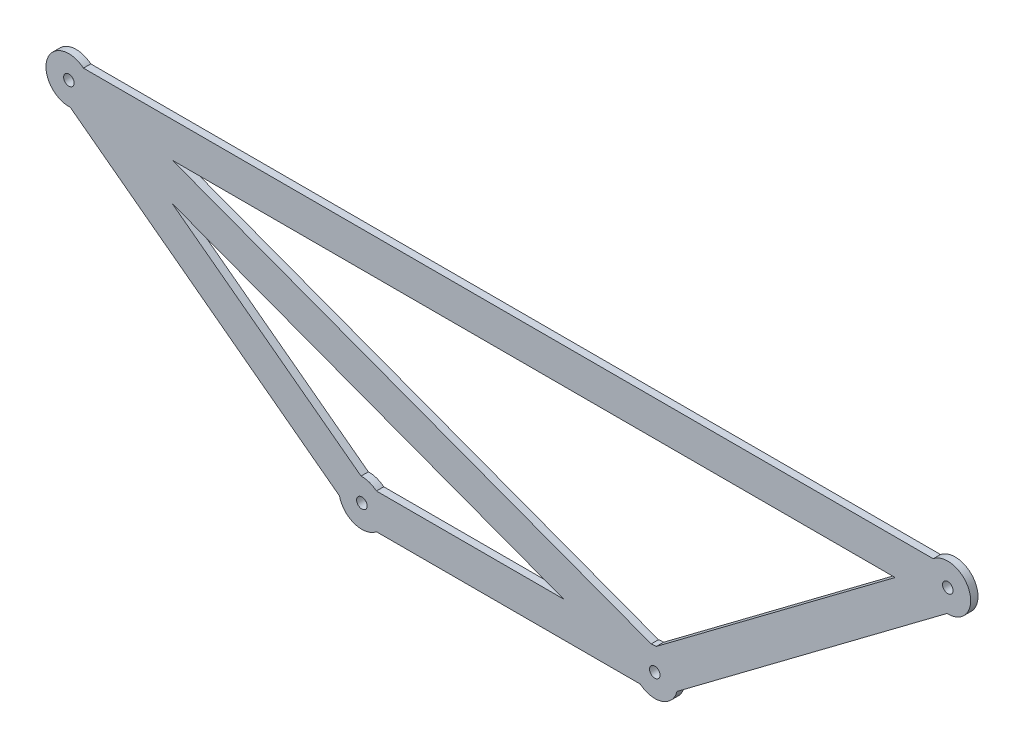
SolidWorks part; units mm, degrees
material "ASTM A36 Steel"
ref_plane "Front Plane" through (0, 0, 0) normal (0, 0, 1) x (1, 0, 0)
ref_plane "Top Plane" through (0, 0, 0) normal (0, 1, 0) x (1, 0, 0)
ref_plane "Right Plane" through (0, 0, 0) normal (1, 0, 0) x (0, 0, -1)
sketch "Sketch2" plane through (0, 0, 0) normal (0, 0, 1) x (1, 0, 0)
  line L0 (0, 0) -> (1200, 0) construction
  line L1 (600, 0) -> (600, -300) construction
  line L2 (400, -300) -> (800, -300) construction
  line L3 (0, 0) -> (400, -300) construction
  line L4 (1200, 0) -> (800, -300) construction
  line L5 (0, 0) -> (800, -300) construction
  line L6 (400, -324.1) -> (800, -324.1)
  line L7 (400, -324.1) -> (400, -275.9)
  line L8 (400, -275.9) -> (800, -275.9)
  line L9 (800, -324.1) -> (800, -275.9)
  line L10 (400, -324.1) -> (800, -275.9) construction
  line L11 (400, -275.9) -> (800, -324.1) construction
  line L12 (0, -24.1) -> (1200, -24.1)
  line L13 (0, -24.1) -> (0, 24.1)
  line L14 (0, 24.1) -> (1200, 24.1)
  line L15 (1200, -24.1) -> (1200, 24.1)
  line L16 (0, -24.1) -> (1200, 24.1) construction
  line L17 (0, 24.1) -> (1200, -24.1) construction
  line L18 (414.6104, -280.5195) -> (14.6104, 19.4805)
  line L19 (414.6104, -280.5195) -> (385.6904, -319.0795)
  line L20 (14.6104, 19.4805) -> (-14.3096, -19.0795)
  line L21 (385.6904, -319.0795) -> (-14.3096, -19.0795)
  line L22 (414.6104, -280.5195) -> (-14.3096, -19.0795) construction
  line L23 (14.6104, 19.4805) -> (385.6904, -319.0795) construction
  line L24 (1185.6877, 19.0831) -> (785.6877, -280.9169)
  line L25 (1185.6877, 19.0831) -> (1214.6077, -19.4769)
  line L26 (785.6877, -280.9169) -> (814.6077, -319.4769)
  line L27 (1214.6077, -19.4769) -> (814.6077, -319.4769)
  line L28 (1185.6877, 19.0831) -> (814.6077, -319.4769) construction
  line L29 (785.6877, -280.9169) -> (1214.6077, -19.4769) construction
  line L30 (792.6095, -319.7081) -> (-7.3905, -19.7081)
  line L31 (792.6095, -319.7081) -> (809.5336, -274.577)
  line L32 (-7.3905, -19.7081) -> (9.5336, 25.423)
  line L33 (809.5336, -274.577) -> (9.5336, 25.423)
  line L34 (792.6095, -319.7081) -> (9.5336, 25.423) construction
  line L35 (-7.3905, -19.7081) -> (809.5336, -274.577) construction
  circle A0 centre (400, -300) radius 31.26
  circle A1 centre (800, -300) radius 31.26
  circle A2 centre (0, 0) radius 31.26
  circle A3 centre (1200, 0) radius 31.26
  point P8 (600, -300)
  point P17 (200.1504, -149.7995)
  point P18 (1000.1477, -150.1969)
  point P23 (401.0716, -147.1425)
  dimension "D10" = 62.52
  dimension "D11" = 62.52
  dimension "D12" = 62.52
  dimension "D13" = 62.52
  dimension "D1" = 1200
  dimension "D2" = 400
  dimension "D3" = 300
  dimension "D4" = 48.2
  dimension "D5" = 48.2
  dimension "D6" = 48.2
  dimension "D7" = 48.2
  dimension "D8" = 48.2
  dimension "D9" = 400
extrude "Boss-Extrude4" add sketch "Sketch2" along normal blind 10 contours A2 | L13 L12 L15 L14 | L30 L31 L33 L32 | L18 L19 L21 L20 | A0 | L7 L6 L9 L8 | A1 | L24 L25 L27 L26 | A3
sketch "Sketch3" plane through (0, 0, 10) normal (0, 0, 1) x (1, 0, 0)
  circle A0 centre (0, 0) radius 7.18
  circle A2 centre (1200, 0) radius 7.18
  circle A4 centre (800, -300) radius 7.18
  circle A5 centre (400, -300) radius 7.18
  dimension "D1" = 14.36
  dimension "D2" = 14.36
  dimension "D3" = 14.36
  dimension "D4" = 14.36
extrude "Cut-Extrude1" cut sketch "Sketch3" against normal blind 10
